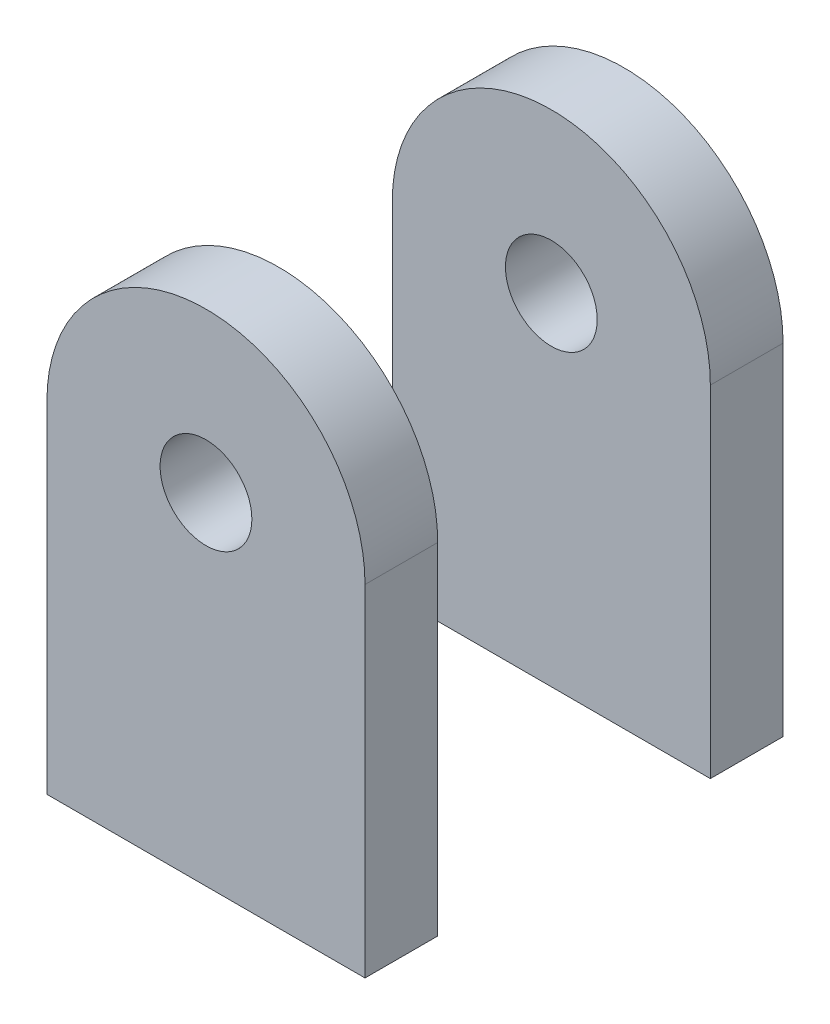
SolidWorks part; units mm, degrees
ref_plane "Front Plane" through (0, 0, 0) normal (0, 0, 1) x (1, 0, 0)
ref_plane "Top Plane" through (0, 0, 0) normal (0, 1, 0) x (1, 0, 0)
ref_plane "Right Plane" through (0, 0, 0) normal (1, 0, 0) x (0, 0, -1)
sketch "Sketch1" plane through (0, 0, 0) normal (0, 0, 1) x (1, 0, 0)
  line L0 (-17.5, 0) -> (17.5, 0)
  line L1 (-17.5, 0) -> (-17.5, 37.5)
  line L2 (17.5, 0) -> (17.5, 37.5)
  arc A0 (-17.5, 37.5) -> (17.5, 37.5) centre (0, 37.5) cw
  circle A1 centre (0, 37.5) radius 5.05
  point P6 (0, 55)
  dimension "D3" = 10.1
  dimension "D1" = 35
  dimension "D2" = 55
extrude "Boss-Extrude1" add sketch "Sketch1" along normal blind 8
ref_plane "Plane1" through (0, 0, -30) normal (0, 0, 1) x (1, 0, 0)
sketch "Sketch2" plane through (0, 0, -30) normal (0, 0, 1) x (1, 0, 0)
  line L0 (17.5, 0) -> (17.5, 37.5) construction
  line L1 (-17.5, 0) -> (17.5, 0) construction
  line L2 (-17.5, 37.5) -> (-17.5, 0) construction
  line L3 (17.5, 0) -> (17.5, 37.5)
  line L4 (-17.5, 0) -> (17.5, 0)
  line L5 (-17.5, 37.5) -> (-17.5, 0)
  circle A0 centre (0, 37.5) radius 5.05 construction
  arc A1 (17.5, 37.5) -> (-17.5, 37.5) centre (0, 37.5) ccw construction
  circle A2 centre (0, 37.5) radius 5.05
  arc A3 (17.5, 37.5) -> (-17.5, 37.5) centre (0, 37.5) ccw
extrude "Boss-Extrude2" add sketch "Sketch2" against normal blind 8 separate body
equation "\"innerDiameter\"=25"
equation "\"chordThickness\"=9.5"
equation "\"chordLength\"=55"
equation "\"chrodDiameter\"=40"
equation "\"ArmLength\"=424"
equation "\"shockMountSpacing\"=30"
equation "\"shockMountHeight\"=55"
equation "\"ShockMountlength\"=35"
equation "\"shockMountAngle\"=40"
equation "\"BoltNominalDiameter\"=10"
equation "\"BushingInnerDiameter\"=10+0.1"
equation "\"D1@Sketch1\"=\"ShockMountlength\""
equation "\"D2@Sketch1\"=\"shockMountHeight\""
